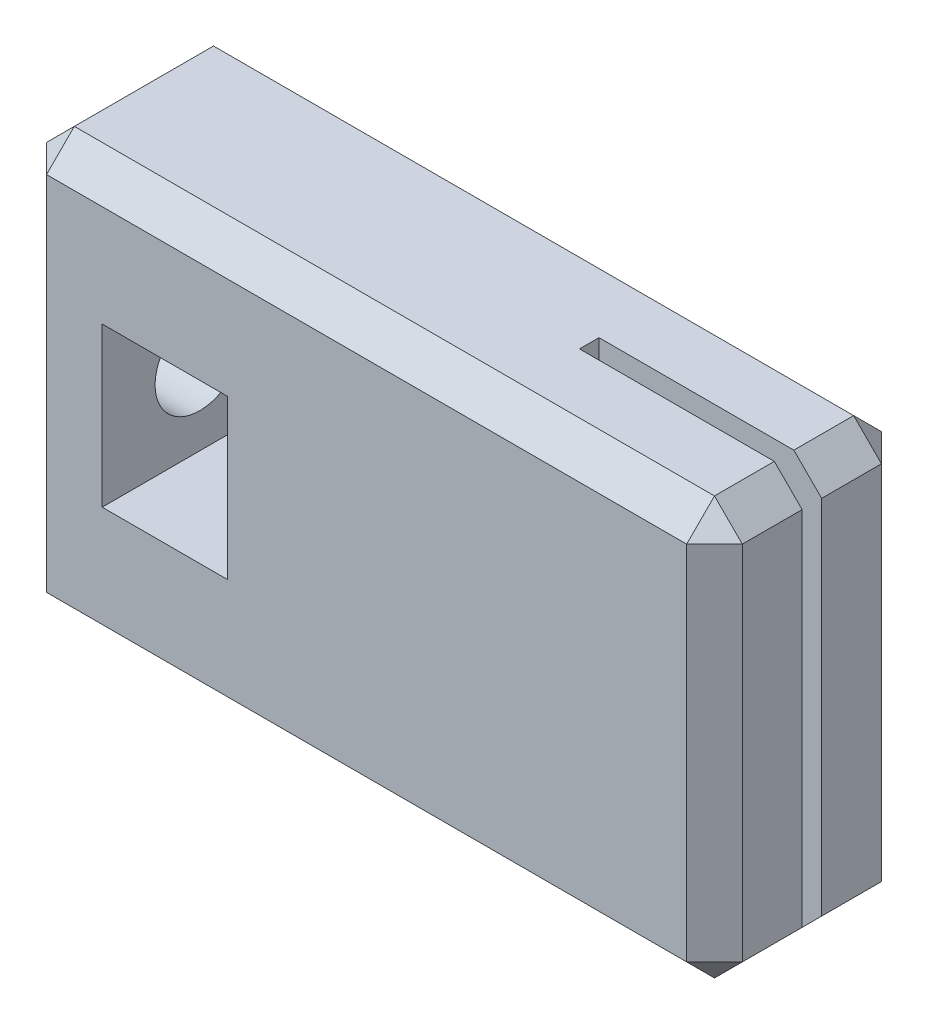
SolidWorks part; units mm, degrees
material "3D printed plastic"
ref_plane "Front Plane" through (0, 0, 0) normal (0, 0, 1) x (1, 0, 0)
ref_plane "Top Plane" through (0, 0, 0) normal (0, 1, 0) x (1, 0, 0)
ref_plane "Right Plane" through (0, 0, 0) normal (1, 0, 0) x (0, 0, -1)
sketch "Sketch2" plane through (0, 0, 0) normal (0, 1, 0) x (1, 0, 0)
  line L0 (25, -0.35) -> (25, -3.5)
  line L1 (0, 3.5) -> (25, 3.5)
  line L2 (0, 3.5) -> (0, -3.5)
  line L3 (0, -3.5) -> (25, -3.5)
  line L4 (25, 3.5) -> (25, 0.35)
  line L5 (25, 0.35) -> (17, 0.35)
  line L7 (25, -0.35) -> (17, -0.35)
  line L8 (17, 0.35) -> (17, -0.35)
  dimension "D1" = 0.7
  dimension "D2" = 7
  dimension "D3" = 25
  dimension "D4" = 8
extrude "Boss-Extrude1" add sketch "Sketch2" along normal mid plane 15
sketch "Sketch3" plane through (0, 0, 0) normal (-1, 0, 0) x (0, 0, 1)
  circle A0 centre (0, 0) radius 1.6
  dimension "D1" = 3.2
extrude "Cut-Extrude1" cut sketch "Sketch3" against normal blind 16
sketch "Sketch4" plane through (0, 0, 3.5) normal (0, 0, 1) x (1, 0, 0)
  line L0 (0, 0) -> (3, 0) construction
  line L1 (3, 2.85) -> (7.5, 2.85)
  line L2 (3, 2.85) -> (3, -2.85)
  line L3 (3, -2.85) -> (7.5, -2.85)
  line L4 (7.5, 2.85) -> (7.5, -2.85)
  dimension "D1" = 3
  dimension "D2" = 4.5
  dimension "D3" = 5.7
extrude "Cut-Extrude2" cut sketch "Sketch4" against normal through all
chamfer "Chamfer1" distance 1 angle 45 14 edges at (0, -7.5, 0) (0, 0, 3.5) (0, 0, -3.5) (25, -7.5, -1.925) (25, 7.5, -1.925) (12.5, -7.5, -3.5) (25, 0, -3.5) (12.5, 7.5, -3.5) (0, 7.5, 0) (25, -7.5, 1.925) (25, 7.5, 1.925) (12.5, -7.5, 3.5) (25, 0, 3.5) (12.5, 7.5, 3.5)
